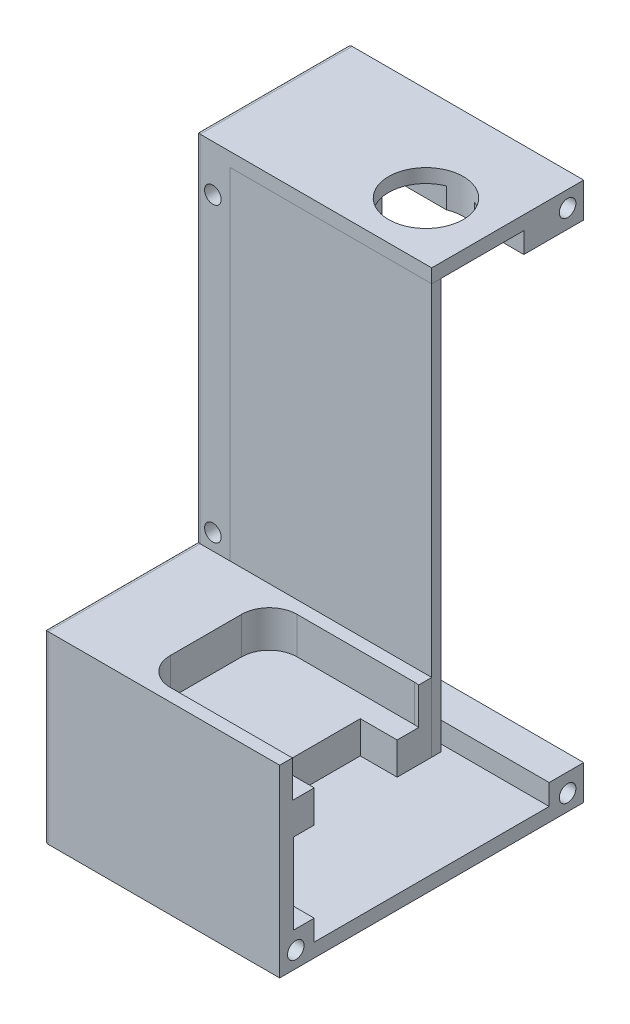
SolidWorks part; units mm, degrees
material "ABS"
ref_plane "Front" through (0, 0, 0) normal (0, 0, 1) x (1, 0, 0)
ref_plane "Top" through (0, 0, 0) normal (0, 1, 0) x (1, 0, 0)
ref_plane "Right" through (0, 0, 0) normal (1, 0, 0) x (0, 0, -1)
sketch "ｽｹｯﾁ1" plane through (0, 0, 0) normal (1, 0, 0) x (0, 0, -1)
  line L0 (23, 92) -> (0, 92)
  line L1 (33, 92) -> (23, 92)
  line L2 (33, 92) -> (33, -25)
  line L3 (33, -25) -> (23, -25)
  line L4 (23, 92) -> (23, -25)
  line L5 (0, 92) -> (0, -25)
  line L6 (0, -25) -> (23, -25)
  line L7 (0, -25) -> (-33, -25)
  line L8 (-33, -25) -> (-33, 0)
  line L9 (-33, 0) -> (0, 0)
  dimension "D1" = 117
  dimension "D2" = 10
  dimension "D3" = 33
  dimension "D4" = 23
  dimension "D5" = 25
extrude "ﾎﾞｽ - 押し出し1" add sketch "ｽｹｯﾁ1" along normal blind 77 contours L9 L8 L7 L5 | L5 L6 L4 L0 | L1 L4 L3 L2
sketch "ｽｹｯﾁ2" plane through (0, 0, -33) normal (0, 0, -1) x (-1, 0, 0)
  line L1 (-7.5, 22.5) -> (-69.5, 22.5)
  line L2 (-7.5, 22.5) -> (-7.5, 84.5)
  line L3 (-7.5, 84.5) -> (-69.5, 84.5)
  line L4 (-69.5, 22.5) -> (-69.5, 84.5)
  line L5 (-7.5, 22.5) -> (-69.5, 84.5) construction
  line L6 (-7.5, 84.5) -> (-69.5, 22.5) construction
  line L8 (0, 92) -> (0, -25) construction
  line L9 (-77, 92) -> (0, 92) construction
  point P0 (-38.5, 53.5)
  dimension "D1" = 62
  dimension "D2" = 62
  dimension "D3" = 7.5
  dimension "D4" = 7.5
extrude "ｶｯﾄ - 押し出し1" cut sketch "ｽｹｯﾁ2" against normal blind 10
sketch "ｽｹｯﾁ3" plane through (0, 92, 0) normal (0, 1, 0) x (1, 0, 0)
  line L1 (0, 33) -> (0, 0) construction
  line L2 (77, 0) -> (0, 0) construction
  circle A0 centre (37.5, 12.5) radius 8.1
  dimension "D1" = 16.2
  dimension "D2" = 37.5
  dimension "D3" = 12.5
extrude "ｶｯﾄ - 押し出し2" cut sketch "ｽｹｯﾁ3" against normal blind 10
sketch "ｽｹｯﾁ4" plane through (0, 0, -33) normal (0, 0, -1) x (-1, 0, 0)
  line L0 (-77, -25) -> (0, -25) construction
  line L1 (-7.5, 22.5) -> (-69.5, 22.5)
  line L2 (-7.5, 22.5) -> (-7.5, -17.5)
  line L3 (-7.5, -17.5) -> (-69.5, -17.5)
  line L4 (-69.5, 22.5) -> (-69.5, -17.5)
  dimension "D1" = 7.5
extrude "ｶｯﾄ - 押し出し3" cut sketch "ｽｹｯﾁ4" against normal offset from surface (58.5 mm away) 7.5 up to face at (38.5, -12.5, 33)
sketch "ｽｹｯﾁ5" plane through (0, 0, 0) normal (0, 1, 0) x (1, 0, 0)
  line L1 (50.25, -2.75) -> (24.75, -2.75)
  line L2 (56.25, -8.75) -> (56.25, -24.25)
  line L3 (50.25, -30.25) -> (24.75, -30.25)
  line L4 (18.75, -8.75) -> (18.75, -24.25)
  line L5 (56.25, -2.75) -> (18.75, -30.25) construction
  line L6 (56.25, -30.25) -> (18.75, -2.75) construction
  line L7 (0, -33) -> (0, 0) construction
  line L11 (77, -33) -> (0, -33)
  line L12 (77, -33) -> (77, 0)
  line L13 (77, 0) -> (0, 0)
  line L14 (0, -33) -> (0, 0)
  arc A0 (18.75, -8.75) -> (24.75, -2.75) centre (24.75, -8.75) cw
  arc A1 (56.25, -8.75) -> (50.25, -2.75) centre (50.25, -8.75) ccw
  arc A2 (56.25, -24.25) -> (50.25, -30.25) centre (50.25, -24.25) cw
  arc A3 (24.75, -30.25) -> (18.75, -24.25) centre (24.75, -24.25) cw
  point P0 (37.5, -16.5)
  dimension "D5" = 6
  dimension "D1" = 27.5
  dimension "D2" = 37.5
  dimension "D3" = 37.5
  dimension "D4" = 2.75
extrude "ﾎﾞｽ - 押し出し2" add sketch "ｽｹｯﾁ5" along normal blind 15
sketch "ｽｹｯﾁ6" plane through (0, 0, 0) normal (0, 1, 0) x (1, 0, 0)
  line L20 (43.25, -30.25) -> (43.25, -2.75)
  line L21 (51.25, -30.25) -> (51.25, -2.8339)
  line L22 (43.25, -25.5) -> (51.25, -25.5)
  line L24 (50.25, -2.75) -> (24.75, -2.75)
  line L25 (56.25, -24.25) -> (56.25, -8.75)
  line L26 (24.75, -30.25) -> (50.25, -30.25)
  line L27 (18.75, -8.75) -> (18.75, -24.25)
  line L28 (50.25, -2.75) -> (24.75, -2.75)
  line L29 (56.25, -24.25) -> (56.25, -8.75)
  line L30 (24.75, -30.25) -> (50.25, -30.25)
  line L31 (18.75, -8.75) -> (18.75, -24.25)
  line L32 (43.25, -7.5) -> (51.25, -7.5)
  arc A21 (24.75, -2.75) -> (18.75, -8.75) centre (24.75, -8.75) ccw
  arc A22 (56.25, -8.75) -> (50.25, -2.75) centre (50.25, -8.75) ccw
  arc A23 (50.25, -30.25) -> (56.25, -24.25) centre (50.25, -24.25) ccw
  arc A24 (18.75, -24.25) -> (24.75, -30.25) centre (24.75, -24.25) ccw
  arc A25 (24.75, -2.75) -> (18.75, -8.75) centre (24.75, -8.75) ccw
  arc A26 (56.25, -8.75) -> (50.25, -2.75) centre (50.25, -8.75) ccw
  arc A27 (50.25, -30.25) -> (56.25, -24.25) centre (50.25, -24.25) ccw
  arc A28 (18.75, -24.25) -> (24.75, -30.25) centre (24.75, -24.25) ccw
  arc M14 (18.8817, -25.5) -> (24.75, -30.25) centre (24.75, -24.25) ccw
  line M15 (24.75, -30.25) -> (50.25, -30.25)
  arc M16 (50.25, -30.25) -> (56.1183, -25.5) centre (50.25, -24.25) ccw
  line M17 (56.1183, -25.5) -> (18.8817, -25.5)
  dimension "D2" = 13
  dimension "D3" = 8
  dimension "D4" = 18
  dimension "D5" = 4.75
  dimension "D1" = 0
extrude "ﾎﾞｽ - 押し出し3" add sketch "ｽｹｯﾁ6" along normal blind 7 contours L31 A28 L20 L28 A25 M17 | L20 M15 M17 M14 | L21 L20 M16 M17 M15 | A27 L29 A26 L21 M17 | L21 M16 M17 | L21 A26 L28 L20 L32
sketch "ｽｹｯﾁ7" plane through (0, 0, 0) normal (0, 0, 1) x (1, 0, 0)
  line L0 (0, 92) -> (0, 15) construction
  line L1 (69.5, 89) -> (7.5, 89)
  line L2 (69.5, 89) -> (69.5, 22.5)
  line L3 (69.5, 22.5) -> (7.5, 22.5)
  line L4 (7.5, 89) -> (7.5, 22.5)
  line L5 (69.5, 89) -> (7.5, 22.5) construction
  line L6 (69.5, 22.5) -> (7.5, 89) construction
  line L7 (77, 92) -> (0, 92) construction
  line L9 (69.5, 22.5) -> (7.5, 22.5) construction
  line L10 (69.5, 84.5) -> (69.5, -17.5) construction
  point P0 (38.5, 55.75)
  dimension "D1" = 7.5
  dimension "D2" = 3
extrude "ｶｯﾄ - 押し出し4" cut sketch "ｽｹｯﾁ7" against normal offset from surface (20 mm away) 3 up to face at (38.5, 53.5, -23)
sketch "ｽｹｯﾁ8" plane through (0, 89, 0) normal (0, -1, 0) x (-1, 0, 0)
  line L0 (-69.5, 20) -> (-69.5, 0) construction
  line L1 (-7.5, 0) -> (-69.5, 0)
  line L2 (-7.5, 0) -> (-7.5, 2)
  line L3 (-7.5, 2) -> (-69.5, 2)
  line L4 (-69.5, 0) -> (-69.5, 2)
  dimension "D1" = 2
extrude "ﾎﾞｽ - 押し出し4" add sketch "ｽｹｯﾁ8" along normal up to vertex (89 mm away) separate body
sketch "ｽｹｯﾁ9" plane through (0, 0, 0) normal (-1, 0, 0) x (0, 0, 1)
  line L0 (-33, 92) -> (0, 92) construction
  line L1 (-33, 92) -> (-33, -25) construction
  line L2 (-33, -25) -> (33, -25) construction
  line L3 (33, -25) -> (33, 15) construction
  circle A0 centre (-29.5, 88.5) radius 1.8
  circle A1 centre (-29.5, -21.5) radius 1.8
  circle A2 centre (29.5, -21.5) radius 1.8
  dimension "D3" = 3.6
  dimension "D5" = 3.5
  dimension "D1" = 3.5
  dimension "D2" = 3.5
  dimension "D4" = 3.5
extrude "ｶｯﾄ - 押し出し5" cut sketch "ｽｹｯﾁ9" against normal through all
sketch "ｽｹｯﾁ10" plane through (0, 0, 0) normal (0, 0, 1) x (1, 0, 0)
  line L0 (77, 92) -> (0, 92) construction
  line L1 (7.5, 15) -> (0, 15) construction
  line L2 (0, 92) -> (0, 15) construction
  line L3 (77, 92) -> (77, 15) construction
  circle A0 centre (3.75, 82) radius 1.8
  circle A1 centre (73.25, 82) radius 1.8
  circle A2 centre (73.25, 18.5) radius 1.8
  circle A3 centre (3.75, 18.5) radius 1.8
  dimension "D3" = 3.6
  dimension "D1" = 3.5
  dimension "D2" = 10
  dimension "D4" = 3.75
  dimension "D5" = 3.75
extrude "ｶｯﾄ - 押し出し6" cut sketch "ｽｹｯﾁ10" against normal through all
sketch "ｽｹｯﾁ12" plane through (0, 0, -23) normal (0, 0, -1) x (-1, 0, 0)
  line L0 (-69.5, 84.5) -> (-69.5, 22.5) construction
  line L1 (-7.5, 84.5) -> (-69.5, 84.5) construction
  circle A0 centre (-66.5, 81.5) radius 1.8
  circle A1 centre (-11.5, 81.5) radius 1.8
  circle A2 centre (-11.5, 26.5) radius 1.8
  circle A3 centre (-66.5, 26.5) radius 1.8
  dimension "D3" = 3.6
  dimension "D1" = 55
  dimension "D2" = 55
  dimension "D4" = 3
  dimension "D5" = 3
extrude "ｶｯﾄ - 押し出し7" cut sketch "ｽｹｯﾁ12" against normal up to next (3 mm away)
sketch "ｽｹｯﾁ13" plane through (0, 0, -33) normal (0, 0, -1) x (-1, 0, 0)
  line L0 (0, 92) -> (0, -25) construction
  line L1 (0, 30.5) -> (-7.5, 30.5)
  line L2 (0, 30.5) -> (0, 42)
  line L3 (0, 42) -> (-7.5, 42)
  line L4 (-7.5, 30.5) -> (-7.5, 42)
  line L5 (-7.5, -17.5) -> (-7.5, 84.5) construction
  line L6 (-69.5, 22.5) -> (-7.5, 22.5) construction
  point P10 (-3.75, 42)
  dimension "D1" = 8
  dimension "D2" = 19.5
extrude "ｶｯﾄ - 押し出し8" cut sketch "ｽｹｯﾁ13" against normal blind 10
sketch "ｽｹｯﾁ15" plane through (77, 0, 0) normal (1, 0, 0) x (0, 0, -1)
  line L12 (0, 15) -> (-33, 15)
  line L13 (-33, 15) -> (-33, -25)
  line L14 (-33, -25) -> (33, -25)
  line L15 (33, -25) -> (33, 92)
  line L16 (33, 92) -> (0, 92)
  line L17 (0, 92) -> (0, 15)
  line L18 (0, 15) -> (-33, 15)
  line L19 (-33, 15) -> (-33, -25)
  line L20 (-33, -25) -> (33, -25)
  line L21 (33, -25) -> (33, 92)
  line L22 (33, 92) -> (0, 92)
  line L23 (0, 92) -> (0, 15)
  dimension "D1" = 0
extrude "ｶｯﾄ - 押し出し9" cut sketch "ｽｹｯﾁ15" against normal blind 25.75
sketch "ｽｹｯﾁ17" plane through (0, -17.5, 0) normal (0, 1, 0) x (1, 0, 0)
  line L0 (51.25, -25.5) -> (51.25, 33) construction
  line L1 (7.5, -25.5) -> (51.25, -25.5)
  line L2 (7.5, -25.5) -> (7.5, 25.5)
  line L3 (7.5, 25.5) -> (51.25, 25.5)
  line L4 (51.25, -25.5) -> (51.25, 25.5)
  line L5 (51.25, 33) -> (7.5, 33) construction
  dimension "D1" = 7.5
extrude "ｶｯﾄ - 押し出し11" cut sketch "ｽｹｯﾁ17" against normal offset from surface (4.5 mm away) 3 up to face at (25.625, -25, 0)
sketch "ｽｹｯﾁ18" plane through (0, 0, 25.5) normal (0, 0, -1) x (-1, 0, 0)
  line L0 (-51.25, 7) -> (-51.25, -22) construction
  line L1 (-7.5, 0) -> (-51.25, 0)
  line L2 (-7.5, 0) -> (-7.5, -17.5)
  line L3 (-7.5, -17.5) -> (-51.25, -17.5)
  line L4 (-51.25, 0) -> (-51.25, -17.5)
  line L6 (-51.25, -25) -> (0, -25) construction
  dimension "D1" = 7.5
extrude "ｶｯﾄ - 押し出し12" cut sketch "ｽｹｯﾁ18" against normal offset from surface (4.5 mm away) 3 up to face at (25.625, -5, 33)
sketch "ｽｹｯﾁ19" plane through (0, 0, -23) normal (0, 0, -1) x (-1, 0, 0)
  line L1 (-51.25, 84.5) -> (-15.5, 84.5)
  line L2 (-51.25, 84.5) -> (-51.25, 22.5)
  line L3 (-51.25, 22.5) -> (-15.5, 22.5)
  line L4 (-15.5, 84.5) -> (-15.5, 22.5)
  line L6 (-7.5, 22.5) -> (-7.5, 30.5) construction
  dimension "D1" = 8
extrude "ｶｯﾄ - 押し出し13" cut sketch "ｽｹｯﾁ19" against normal up to next (3 mm away)
fillet "ﾌｨﾚｯﾄ1" radius 1 10 edges at (0, -5, 33) (0, 15, 16.5) (0, -25, 0) (0, 2.75, -33) (0, 92, -16.5) (0, 67, -33) (0, 42, -28) (0, 30.5, -28) (0, 36.25, -23) (0, 53.5, 0)
